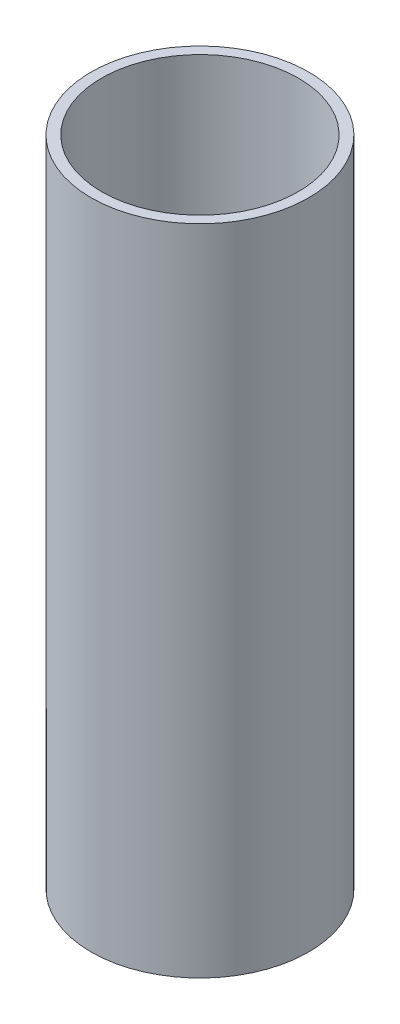
SolidWorks part; units mm, degrees
ref_plane "Front Plane" through (0, 0, 0) normal (0, 0, 1) x (1, 0, 0)
ref_plane "Top Plane" through (0, 0, 0) normal (0, 1, 0) x (1, 0, 0)
ref_plane "Right Plane" through (0, 0, 0) normal (1, 0, 0) x (0, 0, -1)
sketch "Sketch1" plane through (0, 0, 0) normal (0, 1, 0) x (1, 0, 0)
  circle A0 centre (0, 0) radius 25
  circle A1 centre (0, 0) radius 22.6
  dimension "D1" = 50
  dimension "D2" = 45.2
extrude "Boss-Extrude1" add sketch "Sketch1" along normal blind 150
